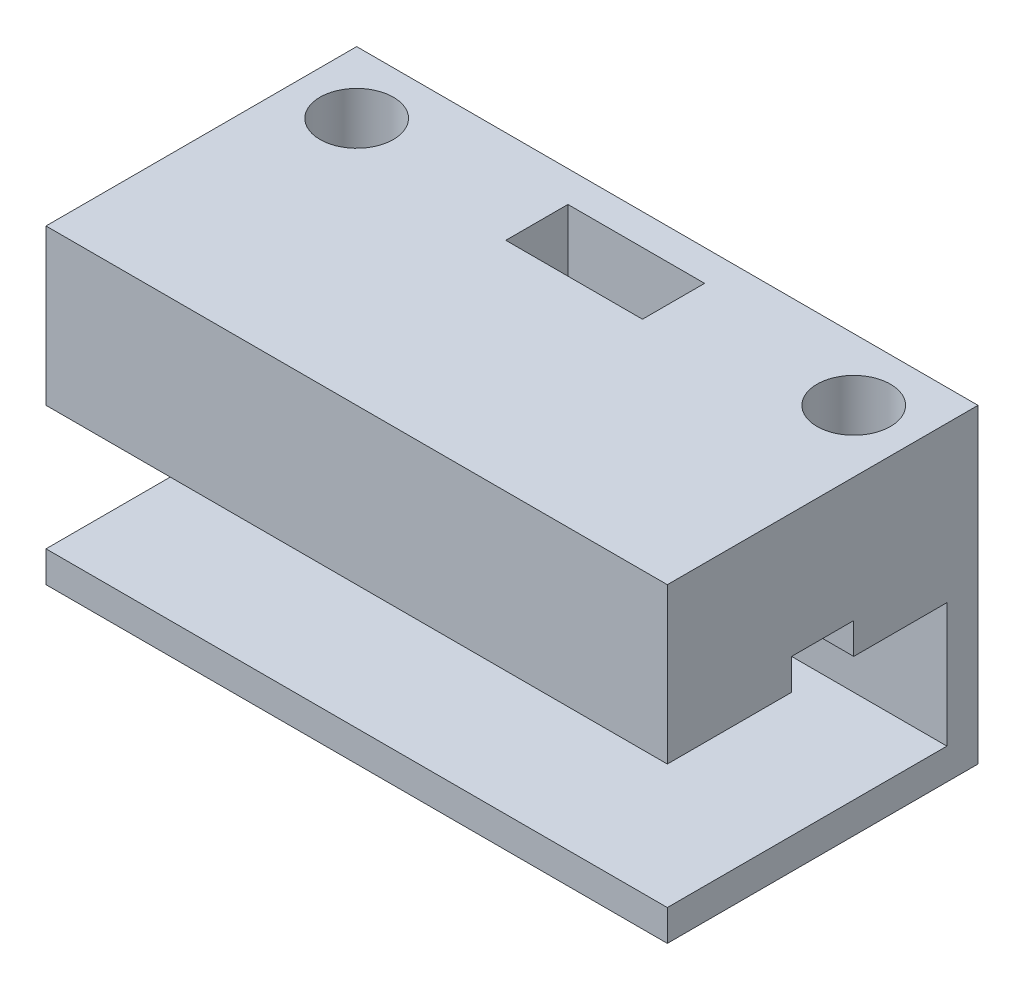
SolidWorks part; units mm, degrees
ref_plane "Front Plane" through (0, 0, 0) normal (0, 0, 1) x (1, 0, 0)
ref_plane "Top Plane" through (0, 0, 0) normal (0, 1, 0) x (1, 0, 0)
ref_plane "Right Plane" through (0, 0, 0) normal (1, 0, 0) x (0, 0, -1)
sketch "Sketch1" plane through (0, 0, 0) normal (0, 0, 1) x (1, 0, 0)
  line L1 (-12.7, -6.35) -> (12.7, -6.35)
  line L2 (-12.7, -6.35) -> (-12.7, 6.35)
  line L3 (-12.7, 6.35) -> (12.7, 6.35)
  line L4 (12.7, -6.35) -> (12.7, 6.35)
  line L5 (-12.7, -6.35) -> (12.7, 6.35) construction
  line L6 (-12.7, 6.35) -> (12.7, -6.35) construction
  point P0 (0, 0)
  dimension "D1" = 25.4
  dimension "D2" = 12.7
extrude "Boss-Extrude1" add sketch "Sketch1" along normal blind 12.7
sketch "Sketch2" plane through (0, 6.35, 0) normal (0, 1, 0) x (1, 0, 0)
  line L0 (12.7, -12.7) -> (-12.7, -12.7) construction
  circle A0 centre (-10.16, -2.54) radius 1.5
  circle A1 centre (10.16, -2.54) radius 1.5
  dimension "D3" = 3
  dimension "D4" = 3
  dimension "D1" = 10.16
  dimension "D2" = 10.16
extrude "Cut-Extrude1" cut sketch "Sketch2" against normal blind 5.08
sketch "Sketch4" plane through (12.7, 0, 0) normal (1, 0, 0) x (0, 0, -1)
  line L0 (-12.7, -6.35) -> (-12.7, 6.35) construction
  line L1 (-12.7, -5.08) -> (-1.27, -5.08)
  line L2 (-12.7, -5.08) -> (-12.7, 0)
  line L3 (-12.7, 0) -> (-1.27, 0)
  line L4 (-1.27, -5.08) -> (-1.27, 0)
  line L5 (0, -6.35) -> (0, 6.35) construction
  line L6 (-12.7, -6.35) -> (0, -6.35) construction
  dimension "D1" = 1.27
  dimension "D2" = 1.27
extrude "Cut-Extrude3" cut sketch "Sketch4" against normal blind 27.432
sketch "Sketch6" plane through (0, 6.35, 0) normal (0, 1, 0) x (1, 0, 0)
  line L0 (0, 0) -> (0, -12.7) construction
  line L1 (12.7, -12.7) -> (-12.7, -12.7) construction
  line L2 (12.7, 0) -> (-12.7, 0) construction
  line L3 (2.794, -1.27) -> (-2.794, -1.27)
  line L4 (2.794, -1.27) -> (2.794, -3.81)
  line L5 (2.794, -3.81) -> (-2.794, -3.81)
  line L6 (-2.794, -1.27) -> (-2.794, -3.81)
  line L7 (2.794, -1.27) -> (-2.794, -3.81) construction
  line L8 (2.794, -3.81) -> (-2.794, -1.27) construction
  point P5 (0, -2.54)
  dimension "D1" = 2.54
  dimension "D2" = 5.588
  dimension "D3" = 1.27
extrude "Cut-Extrude5" cut sketch "Sketch6" against normal blind 9.652
sketch "Sketch7" plane through (12.7, 0, 0) normal (1, 0, 0) x (0, 0, -1)
  line L0 (-1.27, 1.27) -> (-12.7, 1.27) construction
  line L1 (-12.7, 0) -> (-12.7, 6.35) construction
  line L2 (-1.27, 0) -> (-12.7, 0) construction
  line L3 (-1.27, -5.08) -> (-1.27, 0) construction
  line L4 (-5.08, 1.27) -> (-7.62, 1.27)
  line L5 (-5.08, 1.27) -> (-5.08, 0)
  line L6 (-5.08, 0) -> (-7.62, 0)
  line L7 (-7.62, 1.27) -> (-7.62, 0)
  dimension "D1" = 1.27
  dimension "D2" = 2.54
  dimension "D3" = 3.81
extrude "Cut-Extrude6" cut sketch "Sketch7" against normal blind 26.924
